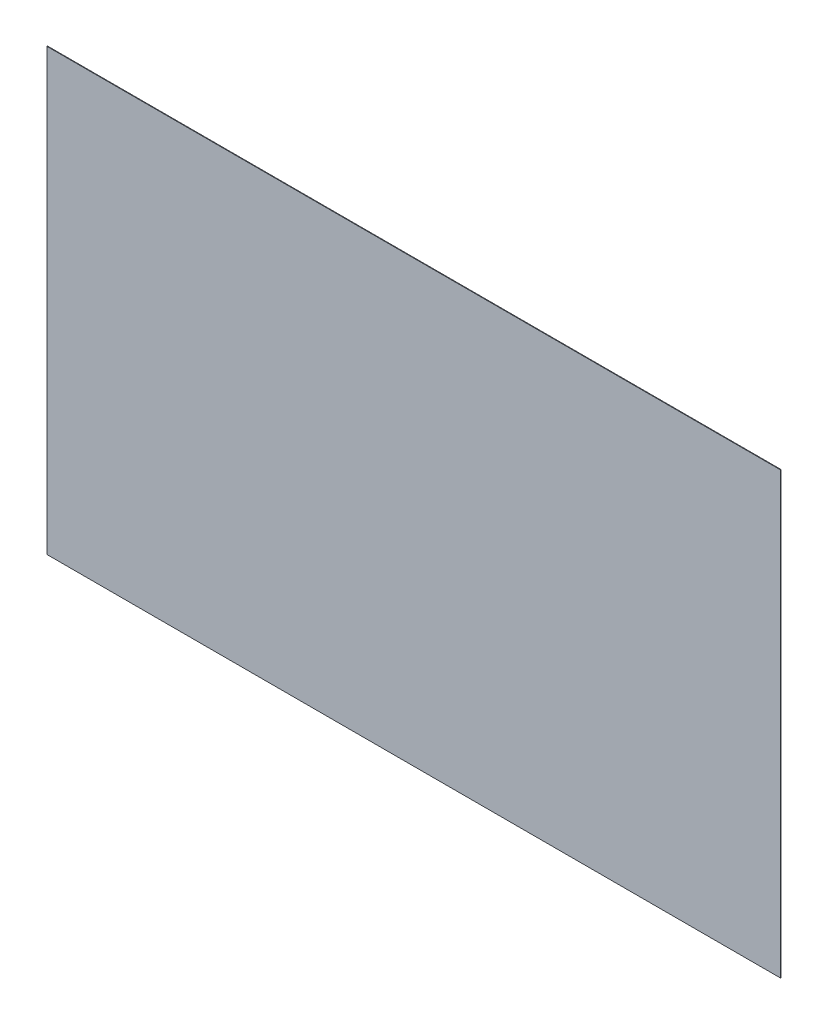
SolidWorks part; units mm, degrees
ref_plane "Front Plane" through (0, 0, 0) normal (0, 0, 1) x (1, 0, 0)
ref_plane "Top Plane" through (0, 0, 0) normal (0, 1, 0) x (1, 0, 0)
ref_plane "Right Plane" through (0, 0, 0) normal (1, 0, 0) x (0, 0, -1)
sketch "Sketch1" plane through (0, 0, 0) normal (0, 0, 1) x (1, 0, 0)
  line L1 (0, 0) -> (1000, 0)
  line L2 (0, 0) -> (0, 600)
  line L3 (0, 600) -> (1000, 600)
  line L4 (1000, 0) -> (1000, 600)
  dimension "D1" = 1000
  dimension "D2" = 600
extrude "Boss-Extrude1" add sketch "Sketch1" along normal blind 0.8
sketch "Sketch2" plane through (0, 0, 0.8) normal (0, 0, 1) x (1, 0, 0)
  line L30 (1000, 0) -> (1000, 600) construction
  line L31 (1000, 600) -> (800, 600)
  line L32 (1000, 600) -> (1000, 400)
  line L33 (1000, 400) -> (800, 400)
  line L34 (800, 600) -> (800, 400)
  line L35 (800, 400) -> (1000, 400)
  line L36 (800, 400) -> (800, 200)
  line L37 (800, 200) -> (1000, 200)
  line L38 (1000, 400) -> (1000, 200)
  line L39 (0, 0) -> (1000, 0) construction
  line L40 (1000, 200) -> (800, 200)
  line L41 (1000, 200) -> (1000, 0)
  line L42 (1000, 0) -> (800, 0)
  line L43 (800, 200) -> (800, 0)
  line L44 (1000, 600) -> (0, 600) construction
  line L45 (800, 600) -> (500, 600)
  line L46 (800, 600) -> (800, 300)
  line L47 (800, 300) -> (500, 300)
  line L48 (500, 600) -> (500, 300)
  line L49 (500, 300) -> (800, 300)
  line L50 (500, 300) -> (500, 0)
  line L51 (500, 0) -> (800, 0)
  line L52 (800, 300) -> (800, 0)
  line L53 (500, 300) -> (200, 300)
  line L54 (500, 300) -> (500, 600)
  line L55 (500, 600) -> (200, 600)
  line L56 (200, 300) -> (200, 600)
  dimension "D1" = 300
  dimension "D2" = 300
  dimension "D3" = 300
  dimension "D4" = 200
  dimension "D5" = 200
  dimension "D6" = 200
  dimension "D7" = 200
